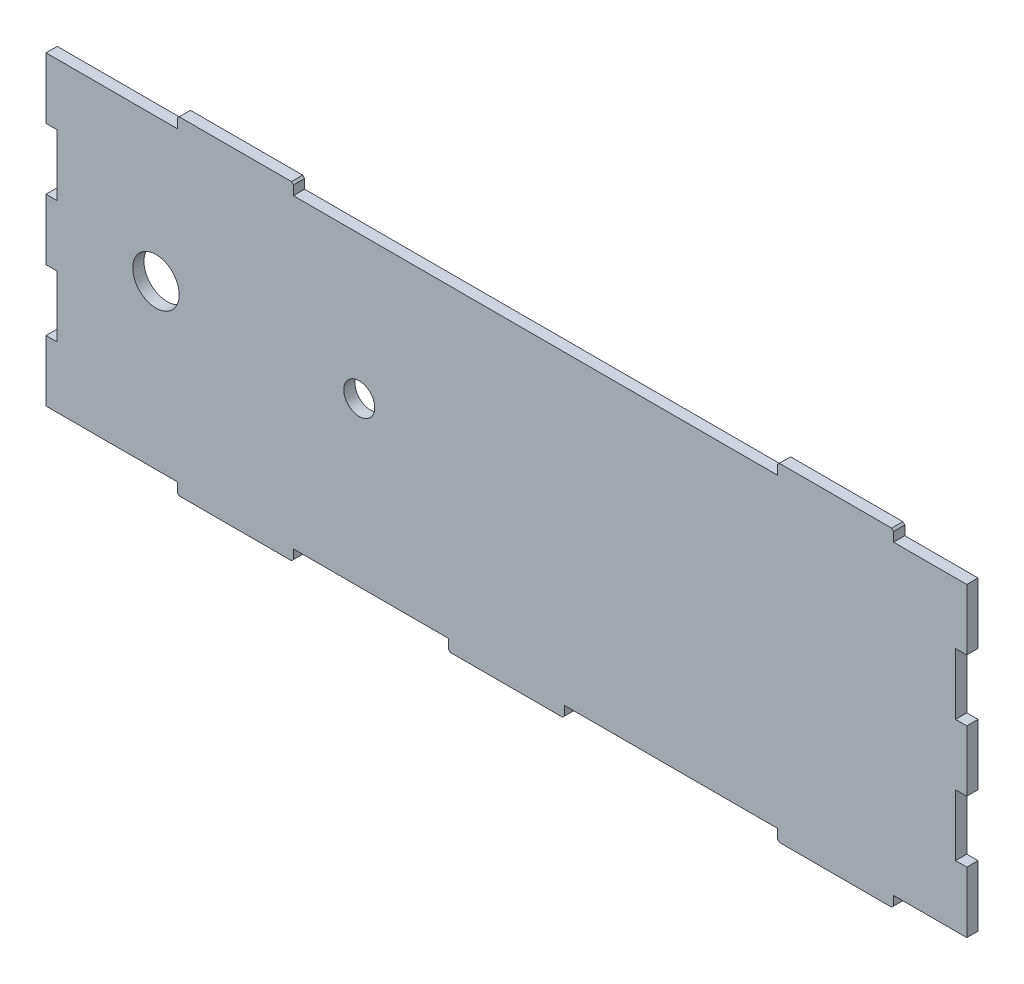
SolidWorks part; units mm, degrees
material "Acrylic (Medium-high impact)"
ref_plane "Front Plane" through (0, 0, 0) normal (0, 0, 1) x (1, 0, 0)
ref_plane "Top Plane" through (0, 0, 0) normal (0, 1, 0) x (1, 0, 0)
ref_plane "Right Plane" through (0, 0, 0) normal (1, 0, 0) x (0, 0, -1)
ref_plane "Plane1" through (0, 0, -137.9) normal (0, 0, 1) x (1, 0, 0)
sketch "Sketch1" plane through (0, 0, -137.9) normal (0, 0, 1) x (1, 0, 0)
  line L0 (118.9, 2.9) -> (100, 2.9)
  line L1 (100, 2.9) -> (100, 0.5)
  line L2 (100, 0.5) -> (99.5, 0)
  line L3 (99.5, 0) -> (70.5, 0)
  line L4 (70.5, 0) -> (70, 0.5)
  line L5 (70, 0.5) -> (70, 2.9)
  line L6 (70, 2.9) -> (15, 2.9)
  line L7 (15, 2.9) -> (15, 0.5)
  line L8 (15, 0.5) -> (14.5, 0)
  line L9 (14.5, 0) -> (-14.5, 0)
  line L10 (-14.5, 0) -> (-15, 0.5)
  line L11 (-15, 0.5) -> (-15, 2.9)
  line L12 (-15, 2.9) -> (-55, 2.9)
  line L13 (-55, 2.9) -> (-55, 0.5)
  line L14 (-55, 0.5) -> (-55.5, 0)
  line L15 (-55.5, 0) -> (-84.5, 0)
  line L16 (-84.5, 0) -> (-85, 0.5)
  line L17 (-85, 0.5) -> (-85, 2.9)
  line L18 (-85, 2.9) -> (-118.9, 2.9)
  line L19 (-118.9, 2.9) -> (-118.9, 18.675)
  line L20 (-118.9, 18.675) -> (-116, 18.675)
  line L21 (-116, 18.675) -> (-116, 34.525)
  line L22 (-116, 34.525) -> (-118.9, 34.525)
  line L23 (-118.9, 34.525) -> (-118.9, 50.275)
  line L24 (-118.9, 50.275) -> (-116, 50.275)
  line L25 (-116, 50.275) -> (-116, 66.125)
  line L26 (-116, 66.125) -> (-118.9, 66.125)
  line L27 (-118.9, 66.125) -> (-118.9, 81.9)
  line L28 (-118.9, 81.9) -> (-85, 81.9)
  line L29 (-85, 81.9) -> (-85, 84.3)
  line L30 (-85, 84.3) -> (-84.5, 84.8)
  line L31 (-84.5, 84.8) -> (-55.5, 84.8)
  line L32 (-55.5, 84.8) -> (-55, 84.3)
  line L33 (-55, 84.3) -> (-55, 81.9)
  line L34 (-55, 81.9) -> (70, 81.9)
  line L35 (70, 81.9) -> (70, 84.3)
  line L36 (70, 84.3) -> (70.5, 84.8)
  line L37 (70.5, 84.8) -> (99.5, 84.8)
  line L38 (99.5, 84.8) -> (100, 84.3)
  line L39 (100, 84.3) -> (100, 81.9)
  line L40 (100, 81.9) -> (118.9, 81.9)
  line L41 (118.9, 81.9) -> (118.9, 66.125)
  line L42 (118.9, 66.125) -> (116, 66.125)
  line L43 (116, 66.125) -> (116, 50.275)
  line L44 (116, 50.275) -> (118.9, 50.275)
  line L45 (118.9, 50.275) -> (118.9, 34.525)
  line L46 (118.9, 34.525) -> (116, 34.525)
  line L47 (116, 34.525) -> (116, 18.675)
  line L48 (116, 18.675) -> (118.9, 18.675)
  line L49 (118.9, 18.675) -> (118.9, 2.9)
  circle A0 centre (-90.5, 45) radius 6
  circle A1 centre (-38, 45) radius 4
extrude "Boss-Extrude1" add sketch "Sketch1" along normal blind 2.9
